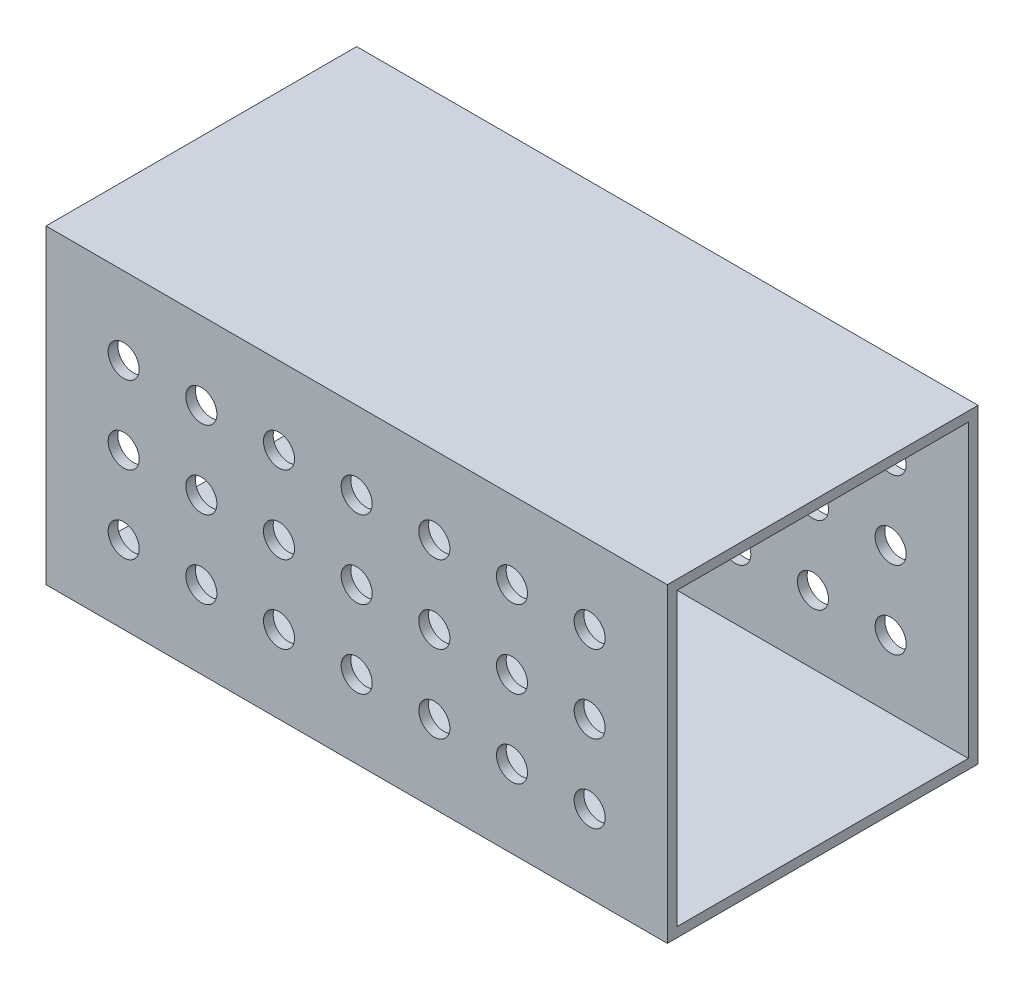
SolidWorks part; units mm, degrees
ref_plane "Front Plane" through (0, 0, 0) normal (0, 0, 1) x (1, 0, 0)
ref_plane "Top Plane" through (0, 0, 0) normal (0, 1, 0) x (1, 0, 0)
ref_plane "Right Plane" through (0, 0, 0) normal (1, 0, 0) x (0, 0, -1)
sketch "Sketch1" plane through (0, 0, 0) normal (1, 0, 0) x (0, 0, -1)
  line L1 (-25.4, -25.4) -> (25.4, -25.4)
  line L2 (-25.4, -25.4) -> (-25.4, 25.4)
  line L3 (-25.4, 25.4) -> (25.4, 25.4)
  line L4 (25.4, -25.4) -> (25.4, 25.4)
  line L5 (-25.4, -25.4) -> (25.4, 25.4) construction
  line L6 (-25.4, 25.4) -> (25.4, -25.4) construction
  line L7 (-23.8125, -23.8125) -> (23.8125, -23.8125)
  line L8 (-23.8125, -23.8125) -> (-23.8125, 23.8125)
  line L9 (-23.8125, 23.8125) -> (23.8125, 23.8125)
  line L10 (23.8125, -23.8125) -> (23.8125, 23.8125)
  line L11 (-23.8125, -23.8125) -> (23.8125, 23.8125) construction
  line L12 (-23.8125, 23.8125) -> (23.8125, -23.8125) construction
  point P0 (0, 0)
  point P7 (0, 0)
  dimension "D1" = 50.8
  dimension "D2" = 50.8
  dimension "D3" = 47.625
extrude "Boss-Extrude1" add sketch "Sketch1" along normal blind 101.6
sketch "Sketch2" plane through (0, 0, 25.4) normal (0, 0, 1) x (1, 0, 0)
  line L0 (-1000, 0) -> (49000, 0) construction
  line L2 (-994.1549, 12.7) -> (49005.8451, 12.7) construction
  line L3 (-984.8446, -12.7) -> (49015.1554, -12.7) construction
  line L4 (101.6, 25.4) -> (0, 25.4) construction
  line L5 (101.6, -25.4) -> (0, -25.4) construction
  line L6 (0, 25.4) -> (0, -25.4) construction
  line L7 (12.7, 12.7) -> (12.7, 0) construction
  line L8 (12.7, 12.7) -> (25.4, 12.7) construction
  circle A24 centre (12.7, 12.7) radius 2.54
  circle A25 centre (12.7, 0) radius 2.54
  circle A26 centre (12.7, -12.7) radius 2.54
  circle A27 centre (25.4, 12.7) radius 2.54
  circle A28 centre (25.4, 0) radius 2.54
  circle A29 centre (25.4, -12.7) radius 2.54
  circle A30 centre (38.1, 12.7) radius 2.54
  circle A31 centre (38.1, 0) radius 2.54
  circle A32 centre (38.1, -12.7) radius 2.54
  circle A33 centre (50.8, 12.7) radius 2.54
  circle A34 centre (50.8, 0) radius 2.54
  circle A35 centre (50.8, -12.7) radius 2.54
  circle A36 centre (63.5, 12.7) radius 2.54
  circle A37 centre (63.5, 0) radius 2.54
  circle A38 centre (63.5, -12.7) radius 2.54
  circle A39 centre (76.2, 12.7) radius 2.54
  circle A40 centre (76.2, 0) radius 2.54
  circle A41 centre (76.2, -12.7) radius 2.54
  circle A42 centre (88.9, 12.7) radius 2.54
  circle A43 centre (88.9, 0) radius 2.54
  circle A44 centre (88.9, -12.7) radius 2.54
  circle A165 centre (101.6, 12.7) radius 2.54 [skipped]
  circle A166 centre (101.6, 0) radius 2.54 [skipped]
  circle A167 centre (101.6, -12.7) radius 2.54 [skipped]
  circle A168 centre (114.3, 12.7) radius 2.54 [skipped]
  circle A169 centre (114.3, 0) radius 2.54 [skipped]
  circle A170 centre (114.3, -12.7) radius 2.54 [skipped]
  circle A171 centre (127, 12.7) radius 2.54 [skipped]
  circle A172 centre (127, 0) radius 2.54 [skipped]
  circle A173 centre (127, -12.7) radius 2.54 [skipped]
  circle A174 centre (139.7, 12.7) radius 2.54 [skipped]
  circle A175 centre (139.7, 0) radius 2.54 [skipped]
  circle A176 centre (139.7, -12.7) radius 2.54 [skipped]
  circle A177 centre (152.4, 12.7) radius 2.54 [skipped]
  circle A178 centre (152.4, 0) radius 2.54 [skipped]
  circle A179 centre (152.4, -12.7) radius 2.54 [skipped]
  circle A180 centre (165.1, 12.7) radius 2.54 [skipped]
  circle A181 centre (165.1, 0) radius 2.54 [skipped]
  circle A182 centre (165.1, -12.7) radius 2.54 [skipped]
  circle A183 centre (177.8, 12.7) radius 2.54 [skipped]
  circle A184 centre (177.8, 0) radius 2.54 [skipped]
  circle A185 centre (177.8, -12.7) radius 2.54 [skipped]
  circle A186 centre (190.5, 12.7) radius 2.54 [skipped]
  circle A187 centre (190.5, 0) radius 2.54 [skipped]
  circle A188 centre (190.5, -12.7) radius 2.54 [skipped]
  circle A189 centre (203.2, 12.7) radius 2.54 [skipped]
  circle A190 centre (203.2, 0) radius 2.54 [skipped]
  circle A191 centre (203.2, -12.7) radius 2.54 [skipped]
  circle A192 centre (215.9, 12.7) radius 2.54 [skipped]
  circle A193 centre (215.9, 0) radius 2.54 [skipped]
  circle A194 centre (215.9, -12.7) radius 2.54 [skipped]
  circle A195 centre (228.6, 12.7) radius 2.54 [skipped]
  circle A196 centre (228.6, 0) radius 2.54 [skipped]
  circle A197 centre (228.6, -12.7) radius 2.54 [skipped]
  circle A198 centre (241.3, 12.7) radius 2.54 [skipped]
  circle A199 centre (241.3, 0) radius 2.54 [skipped]
  circle A200 centre (241.3, -12.7) radius 2.54 [skipped]
  circle A201 centre (254, 12.7) radius 2.54 [skipped]
  circle A202 centre (254, 0) radius 2.54 [skipped]
  circle A203 centre (254, -12.7) radius 2.54 [skipped]
  circle A204 centre (266.7, 12.7) radius 2.54 [skipped]
  circle A205 centre (266.7, 0) radius 2.54 [skipped]
  circle A206 centre (266.7, -12.7) radius 2.54 [skipped]
  circle A207 centre (279.4, 12.7) radius 2.54 [skipped]
  circle A208 centre (279.4, 0) radius 2.54 [skipped]
  circle A209 centre (279.4, -12.7) radius 2.54 [skipped]
  circle A210 centre (292.1, 12.7) radius 2.54 [skipped]
  circle A211 centre (292.1, 0) radius 2.54 [skipped]
  circle A212 centre (292.1, -12.7) radius 2.54 [skipped]
  circle A213 centre (304.8, 12.7) radius 2.54 [skipped]
  circle A214 centre (304.8, 0) radius 2.54 [skipped]
  circle A215 centre (304.8, -12.7) radius 2.54 [skipped]
  circle A216 centre (317.5, 12.7) radius 2.54 [skipped]
  circle A217 centre (317.5, 0) radius 2.54 [skipped]
  circle A218 centre (317.5, -12.7) radius 2.54 [skipped]
  circle A219 centre (330.2, 12.7) radius 2.54 [skipped]
  circle A220 centre (330.2, 0) radius 2.54 [skipped]
  circle A221 centre (330.2, -12.7) radius 2.54 [skipped]
  circle A222 centre (342.9, 12.7) radius 2.54 [skipped]
  circle A223 centre (342.9, 0) radius 2.54 [skipped]
  circle A224 centre (342.9, -12.7) radius 2.54 [skipped]
  circle A225 centre (355.6, 12.7) radius 2.54 [skipped]
  circle A226 centre (355.6, 0) radius 2.54 [skipped]
  circle A227 centre (355.6, -12.7) radius 2.54 [skipped]
  circle A228 centre (368.3, 12.7) radius 2.54 [skipped]
  circle A229 centre (368.3, 0) radius 2.54 [skipped]
  circle A230 centre (368.3, -12.7) radius 2.54 [skipped]
  circle A231 centre (381, 12.7) radius 2.54 [skipped]
  circle A232 centre (381, 0) radius 2.54 [skipped]
  circle A233 centre (381, -12.7) radius 2.54 [skipped]
  circle A234 centre (393.7, 12.7) radius 2.54 [skipped]
  circle A235 centre (393.7, 0) radius 2.54 [skipped]
  circle A236 centre (393.7, -12.7) radius 2.54 [skipped]
  circle A237 centre (406.4, 12.7) radius 2.54 [skipped]
  circle A238 centre (406.4, 0) radius 2.54 [skipped]
  circle A239 centre (406.4, -12.7) radius 2.54 [skipped]
  circle A240 centre (419.1, 12.7) radius 2.54 [skipped]
  circle A241 centre (419.1, 0) radius 2.54 [skipped]
  circle A242 centre (419.1, -12.7) radius 2.54 [skipped]
  circle A243 centre (431.8, 12.7) radius 2.54 [skipped]
  circle A244 centre (431.8, 0) radius 2.54 [skipped]
  circle A245 centre (431.8, -12.7) radius 2.54 [skipped]
  circle A246 centre (444.5, 12.7) radius 2.54 [skipped]
  circle A247 centre (444.5, 0) radius 2.54 [skipped]
  circle A248 centre (444.5, -12.7) radius 2.54 [skipped]
  circle A249 centre (457.2, 12.7) radius 2.54 [skipped]
  circle A250 centre (457.2, 0) radius 2.54 [skipped]
  circle A251 centre (457.2, -12.7) radius 2.54 [skipped]
  circle A252 centre (469.9, 12.7) radius 2.54 [skipped]
  circle A253 centre (469.9, 0) radius 2.54 [skipped]
  circle A254 centre (469.9, -12.7) radius 2.54 [skipped]
  circle A255 centre (482.6, 12.7) radius 2.54 [skipped]
  circle A256 centre (482.6, 0) radius 2.54 [skipped]
  circle A257 centre (482.6, -12.7) radius 2.54 [skipped]
  circle A258 centre (495.3, 12.7) radius 2.54 [skipped]
  circle A259 centre (495.3, 0) radius 2.54 [skipped]
  circle A260 centre (495.3, -12.7) radius 2.54 [skipped]
  circle A261 centre (508, 12.7) radius 2.54 [skipped]
  circle A262 centre (508, 0) radius 2.54 [skipped]
  circle A263 centre (508, -12.7) radius 2.54 [skipped]
  circle A264 centre (520.7, 12.7) radius 2.54 [skipped]
  circle A265 centre (520.7, 0) radius 2.54 [skipped]
  circle A266 centre (520.7, -12.7) radius 2.54 [skipped]
  circle A267 centre (533.4, 12.7) radius 2.54 [skipped]
  circle A268 centre (533.4, 0) radius 2.54 [skipped]
  circle A269 centre (533.4, -12.7) radius 2.54 [skipped]
  circle A270 centre (546.1, 12.7) radius 2.54 [skipped]
  circle A271 centre (546.1, 0) radius 2.54 [skipped]
  circle A272 centre (546.1, -12.7) radius 2.54 [skipped]
  circle A273 centre (558.8, 12.7) radius 2.54 [skipped]
  circle A274 centre (558.8, 0) radius 2.54 [skipped]
  circle A275 centre (571.5, 12.7) radius 2.54 [skipped]
  circle A276 centre (571.5, 0) radius 2.54 [skipped]
  circle A277 centre (571.5, -12.7) radius 2.54 [skipped]
  circle A278 centre (584.2, 12.7) radius 2.54 [skipped]
  circle A279 centre (584.2, 0) radius 2.54 [skipped]
  circle A280 centre (584.2, -12.7) radius 2.54 [skipped]
  circle A281 centre (596.9, 12.7) radius 2.54 [skipped]
  circle A282 centre (596.9, 0) radius 2.54 [skipped]
  circle A283 centre (596.9, -12.7) radius 2.54 [skipped]
  circle A284 centre (558.8, -12.7) radius 2.54 [skipped]
  dimension "D1" = 12.7
  dimension "D3" = 5.08
  dimension "D2" = 12.7
  dimension "D4" = 12.7
  dimension "D6" = 12.7
  dimension "D8" = 12.7
  dimension "D5" = 3
  dimension "D7" = 47
extrude "Cut-Extrude2" cut sketch "Sketch2" against normal blind 609.6
